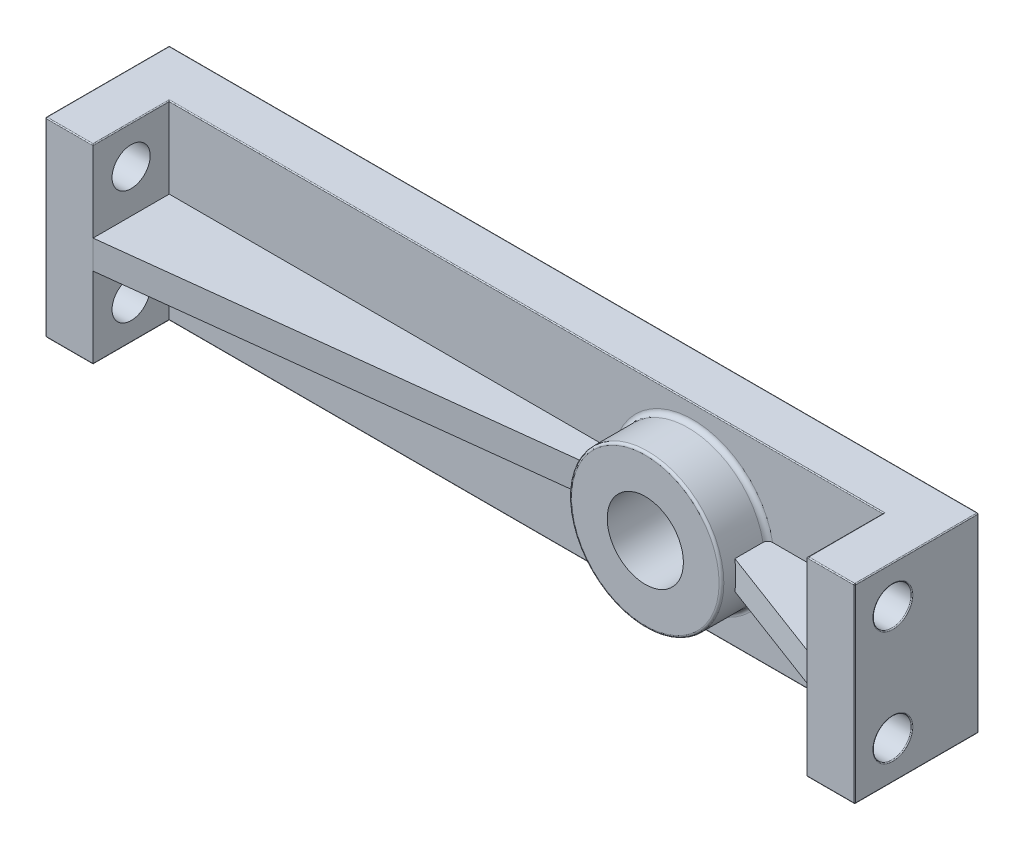
SolidWorks part; units mm, degrees
ref_plane "Front Plane" through (0, 0, 0) normal (0, 0, 1) x (1, 0, 0)
ref_plane "Top Plane" through (0, 0, 0) normal (0, 1, 0) x (1, 0, 0)
ref_plane "Right Plane" through (0, 0, 0) normal (1, 0, 0) x (0, 0, -1)
sketch "Sketch1" plane through (0, 0, 0) normal (0, 1, 0) x (1, 0, 0)
  line L0 (-952.5, 0) -> (952.5, 0)
  line L1 (-952.5, 0) -> (-952.5, -203.2)
  line L2 (-952.5, -203.2) -> (-1079.5, -203.2)
  line L3 (-1079.5, -203.2) -> (-1079.5, 127)
  line L4 (-1079.5, 127) -> (1079.5, 127)
  line L5 (1079.5, 127) -> (1079.5, -203.2)
  line L6 (1079.5, -203.2) -> (952.5, -203.2)
  line L7 (952.5, -203.2) -> (952.5, 0)
  point P4 (0, 0)
  dimension "D1" = 127
  dimension "D2" = 127
  dimension "D3" = 330.2
  dimension "D4" = 330.2
  dimension "D5" = 127
  dimension "D6" = 2159
extrude "Boss-Extrude1" add sketch "Sketch1" along normal mid plane 508
sketch "Sketch2" plane through (0, 0, 0) normal (0, 1, 0) x (1, 0, 0)
  line L0 (-952.5, -203.2) -> (-952.5, 0) construction
  line L1 (-952.5, -203.2) -> (-952.5, 0)
  line L2 (-952.5, -203.2) -> (241.3, -63.5)
  line L3 (241.3, -63.5) -> (241.3, 0)
  line L4 (-952.5, 0) -> (952.5, 0) construction
  line L5 (241.3, 0) -> (-952.5, 0)
  line L6 (952.5, 0) -> (952.5, -203.2) construction
  line L7 (952.5, 0) -> (952.5, -203.2)
  line L8 (952.5, -203.2) -> (647.7, -88.9)
  line L9 (647.7, -88.9) -> (647.7, 0)
  line L10 (647.7, 0) -> (952.5, 0)
  dimension "D1" = 1193.8
  dimension "D2" = 63.5
  dimension "D3" = 304.8
  dimension "D4" = 88.9
extrude "Boss-Extrude2" add sketch "Sketch2" along normal mid plane 76.2
sketch "Sketch4" plane through (0, 0, 0) normal (0, 0, 1) x (1, 0, 0)
  line L0 (241.3, 38.1) -> (241.3, -38.1) construction
  circle A0 centre (444.5, 0) radius 101.6
  dimension "D1" = 203.2
  dimension "D2" = 203.2
extrude "Cut-Extrude1" cut sketch "Sketch4" against normal through all
sketch "Sketch10" plane through (0, 0, 0) normal (0, 0, 1) x (1, 0, 0)
  line L0 (647.7, 38.1) -> (647.7, -38.1) construction
  line L2 (647.7, 38.1) -> (647.7, -38.1)
  line L3 (241.3, 38.1) -> (241.3, -38.1)
  line L4 (241.3, -38.1) -> (244.9038, -38.1)
  line L5 (241.3, 38.1) -> (244.9038, 38.1)
  line L6 (647.7, 38.1) -> (644.0962, 38.1)
  line L7 (647.7, -38.1) -> (644.0962, -38.1)
  arc A0 (244.9038, 38.1) -> (244.9038, -38.1) centre (444.5, 0) ccw
  arc A1 (244.9038, 38.1) -> (244.9038, -38.1) centre (444.5, 0) ccw
  arc A2 (644.0962, -38.1) -> (644.0962, 38.1) centre (444.5, 0) ccw
  line M9 (241.3, 38.1) -> (241.3, -38.1)
  dimension "D1" = 406.4
extrude "Boss-Extrude11" add sketch "Sketch10" along normal up to surface (63.5 mm away) contours A0 L5 M9 | A0 L3 L4
sketch "Sketch11" plane through (0, 0, 0) normal (0, 0, 1) x (1, 0, 0)
  line L0 (647.7, 38.1) -> (647.7, -38.1) construction
  line L1 (647.7, 38.1) -> (647.7, -38.1)
  line L2 (647.7, 38.1) -> (644.0962, 38.1)
  line L3 (647.7, -38.1) -> (644.0962, -38.1)
  arc A0 (644.0962, -38.1) -> (644.0962, 38.1) centre (444.5, 0) ccw
  point P0 (444.5, 0)
  line M10 (647.7, -38.1) -> (647.7, 38.1)
  dimension "D1" = 406.4
extrude "Boss-Extrude12" add sketch "Sketch11" along normal up to surface (88.9 mm away) contours A0 L1 L2 | A0 L3 M10
sketch "Sketch12" plane through (0, 0, 0) normal (0, 0, 1) x (1, 0, 0)
  circle A0 centre (444.5, 0) radius 203.2
  arc M3 (644.0962, -38.1) -> (644.0962, 38.1) centre (444.5, 0) ccw
  arc M9 (244.9038, 38.1) -> (244.9038, -38.1) centre (444.5, 0) ccw
  circle M14 centre (444.5, 0) radius 101.6
  dimension "D1" = 406.4
extrude "Boss-Extrude13" add sketch "Sketch12" along normal blind 127 contours A0 M3 M9 M14
sketch "Sketch19" plane through (1079.5, 0, 0) normal (1, 0, 0) x (0, 0, -1)
  line L0 (0, 0) -> (-330.2564, 0) construction
  line L1 (-203.2, 254) -> (-203.2, -254) construction
  circle A0 centre (-101.6, 152.4) radius 50.8
  circle A1 centre (-101.6, -152.4) radius 50.8
  dimension "D1" = 101.6
  dimension "D2" = 152.4
  dimension "D3" = 152.4
  dimension "D4" = 101.6
extrude "Cut-Extrude3" cut sketch "Sketch19" against normal up to surface (2032 mm away)
sketch "Sketch21" plane through (-1079.5, 0, 0) normal (-1, 0, 0) x (0, 0, 1)
  circle A0 centre (101.6, 152.4) radius 50.8
  circle A1 centre (101.6, -152.4) radius 50.8
  dimension "D1" = 101.6
  dimension "D2" = 152.4
  dimension "D3" = 152.4
  dimension "D4" = 101.6
extrude "Cut-Extrude4" cut sketch "Sketch21" against normal up to surface (127 mm away) up to face at (-952.5, 146.05, 101.6)
fillet "Fillet1" radius 2.54 25 edges at (1016, 254, 203.2) (952.5, 254, 101.6) (0, 254, 0) (-952.5, 254, 101.6) (-1016, 254, 203.2) (1079.5, 0, 203.2) (1079.5, 254, 38.1) (1079.5, -152.4, 50.8) (1079.5, 152.4, 50.8) (-1016, -254, 203.2) (-952.5, -254, 101.6) (0, -254, 0) (952.5, -254, 101.6) (1016, -254, 203.2) (1079.5, -254, 38.1) (-1079.5, 254, 38.1) (-1079.5, 0, 203.2) (-1079.5, -254, 38.1) (-1079.5, -152.4, 152.4) (-1079.5, 152.4, 152.4) (1079.5, 0, -127) (0, 254, -127) (-1079.5, 0, -127) (0, -254, -127) (546.1, 0, -127)
fillet "Fillet2" radius 6.35 1 edges at (647.7, 0, 127)
fillet "Fillet3" radius 12.7 2 edges at (444.5, 203.2, 0) (444.5, -203.2, 0)
